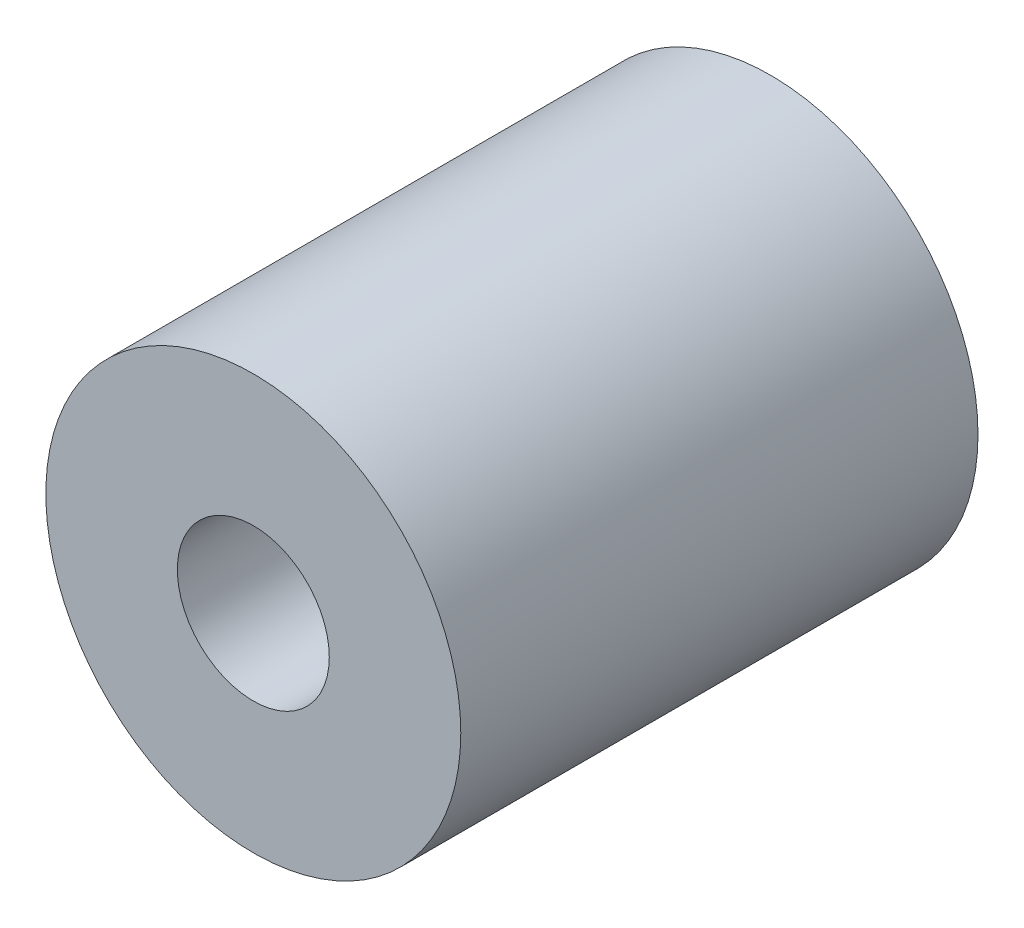
SolidWorks part; units mm, degrees
material "Paraffina"
ref_plane "Piano frontale" through (0, 0, 0) normal (0, 0, 1) x (1, 0, 0)
ref_plane "Piano superiore" through (0, 0, 0) normal (0, 1, 0) x (1, 0, 0)
ref_plane "Piano destro" through (0, 0, 0) normal (1, 0, 0) x (0, 0, -1)
sketch "Schizzo1" plane through (0, 0, 0) normal (0, 0, 1) x (1, 0, 0)
  circle A0 centre (0, 0) radius 71
  circle A1 centre (0, 0) radius 26
  dimension "D1" = 52
  dimension "D2" = 142
extrude "Estrusione-Estrusione1" add sketch "Schizzo1" along normal blind 177
